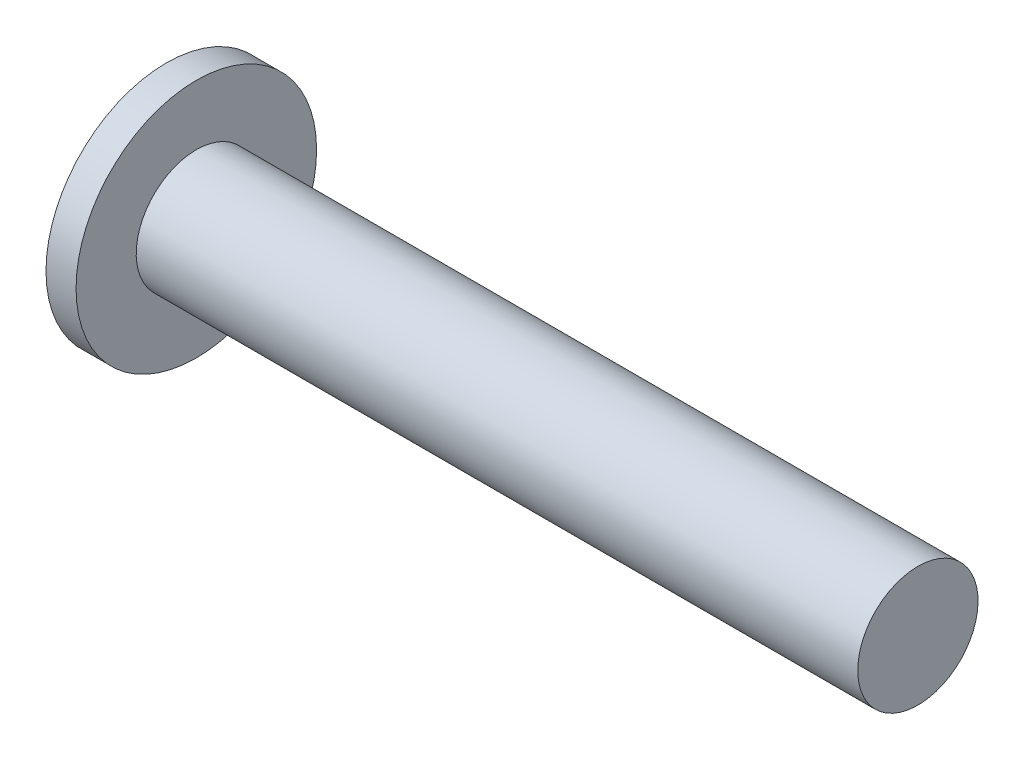
SolidWorks part; units mm, degrees
ref_plane "Front Plane" through (0, 0, 0) normal (0, 0, 1) x (1, 0, 0)
ref_plane "Top Plane" through (0, 0, 0) normal (0, 1, 0) x (1, 0, 0)
ref_plane "Right Plane" through (0, 0, 0) normal (1, 0, 0) x (0, 0, -1)
sketch "Sketch4" plane through (0, 0, 0) normal (0, 0, 1) x (1, 0, 0)
  line L0 (0, 0) -> (0, 40)
  line L1 (0, 40) -> (10, 40)
  line L2 (10, 40) -> (10, 20)
  line L3 (10, 20) -> (250, 20)
  line L4 (250, 20) -> (250, 0)
  line L5 (250, 0) -> (0, 0)
  dimension "D1" = 20
  dimension "D2" = 40
  dimension "D3" = 10
  dimension "D4" = 250
revolve "Revolve1" add sketch "Sketch4" angle 360 about L5
